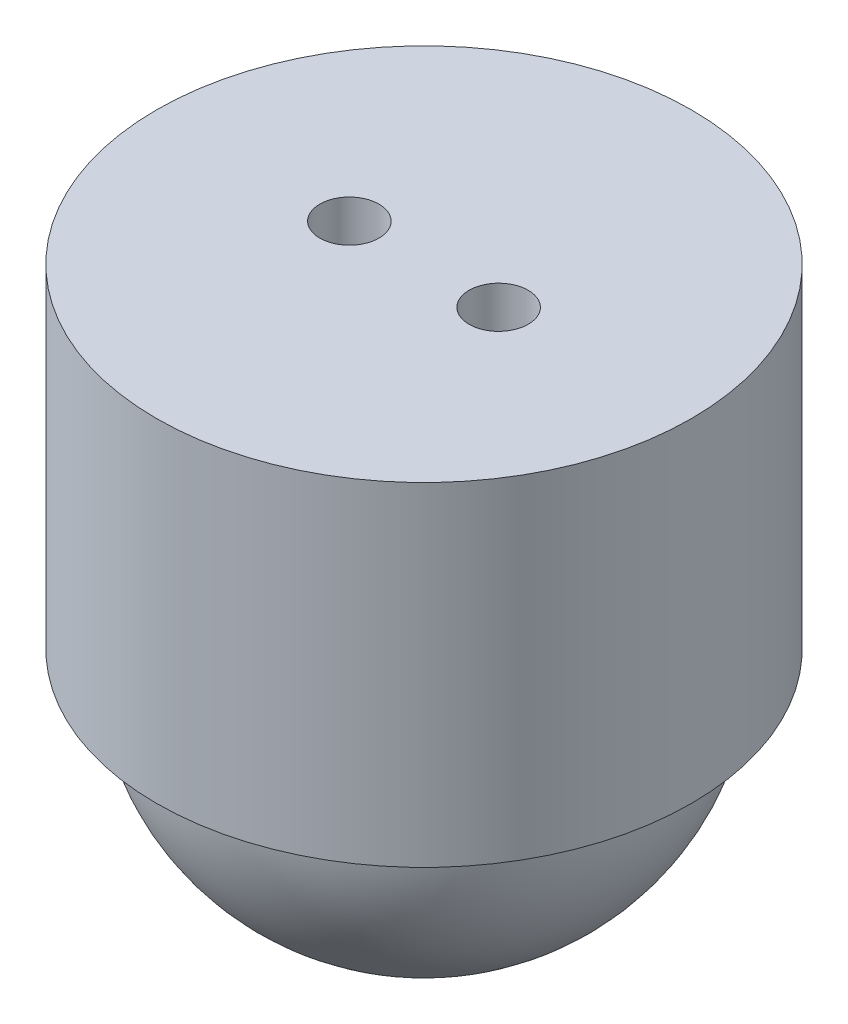
SolidWorks part; units mm, degrees
ref_plane "Alzado" through (0, 0, 0) normal (0, 0, 1) x (1, 0, 0)
ref_plane "Planta" through (0, 0, 0) normal (0, 1, 0) x (1, 0, 0)
ref_plane "Vista lateral" through (0, 0, 0) normal (1, 0, 0) x (0, 0, -1)
sketch "Croquis1" plane through (0, 0, 0) normal (0, 0, 1) x (1, 0, 0)
  line L0 (-9.5, 0) -> (9.5, 0)
  arc A0 (9.5, 0) -> (-9.5, 0) centre (0, 0) ccw
  dimension "D1" = 9.5
revolve "Revolución1" add sketch "Croquis1" angle 360 about L0
sketch "Croquis7" plane through (0, 0, 0) normal (0, 1, 0) x (1, 0, 0)
  circle A0 centre (0, 0) radius 10.922
  dimension "D1" = 21.844
extrude "Saliente-Extruir2" add sketch "Croquis7" along normal blind 13.614
sketch "Croquis8" plane through (0, 13.614, 0) normal (0, 1, 0) x (1, 0, 0)
  line L0 (0, 10.922) -> (0, -10.922) construction
  line L1 (-10.922, 0) -> (10.922, 0) construction
  circle A0 centre (0, 0) radius 10.922 construction
  circle A1 centre (-3.048, 0) radius 1.2065
  circle A2 centre (3.048, 0) radius 1.2065
  dimension "D2" = 2.413
  dimension "D1" = 3.048
extrude "Cortar-Extruir3" cut sketch "Croquis8" against normal blind 13.614
